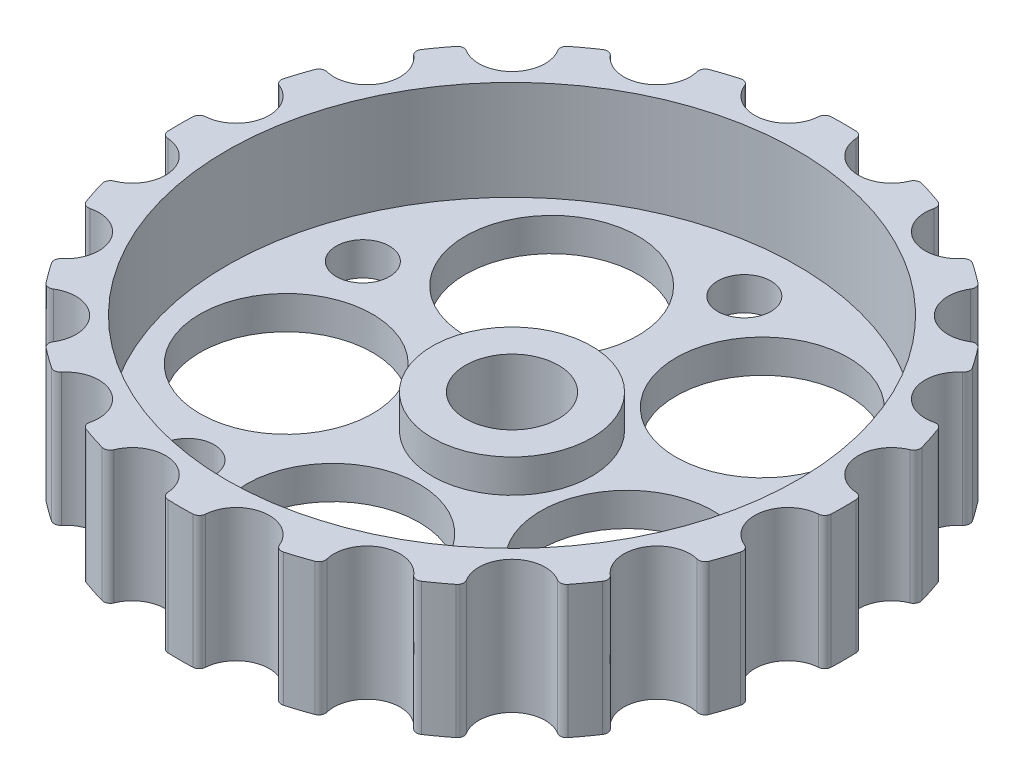
SolidWorks part; units mm, degrees
ref_plane "Спереди" through (0, 0, 0) normal (0, 0, 1) x (1, 0, 0)
ref_plane "Сверху" through (0, 0, 0) normal (0, 1, 0) x (1, 0, 0)
ref_plane "Справа" through (0, 0, 0) normal (1, 0, 0) x (0, 0, -1)
sketch "Эскиз1" plane through (0, 0, 0) normal (0, 0, 1) x (1, 0, 0)
  line L1 (50, -10) -> (0, -10)
  line L2 (50, -10) -> (50, 10)
  line L3 (50, 10) -> (0, 10)
  line L4 (0, -10) -> (0, 10)
  line L5 (50, -10) -> (0, 10) construction
  line L6 (50, 10) -> (0, -10) construction
  point P0 (25, 0)
  dimension "D1" = 20
  dimension "D2" = 50
revolve "Повернуть1" add sketch "Эскиз1" angle 360 about L4
sketch "Эскиз2" plane through (0, 10, 0) normal (0, 1, 0) x (1, 0, 0)
  line L0 (0, 50) -> (0, 0) construction
  line L1 (0, 0) -> (35.3553, 35.3553) construction
  circle A0 centre (0, 0) radius 50 construction
  dimension "D1" = 45
ref_plane "Плоскость1" through (0, 0, 0) normal (0.7071, 0, 0.7071) x (0.7071, 0, -0.7071)
sketch "Эскиз3" plane through (0, 0, 0) normal (0.7071, 0, 0.7071) x (0.7071, 0, -0.7071)
  line L0 (50, -10) -> (50, 10) construction
  line L1 (45, -10) -> (55, -10) construction
  line L2 (45, -10) -> (45, 10) construction
  line L3 (45, 10) -> (55, 10) construction
  line L4 (55, -10) -> (55, 10)
  line L5 (45, -10) -> (55, 10) construction
  line L6 (45, 10) -> (55, -10) construction
  line L7 (0, 10) -> (50, 10) construction
  line L8 (50, 10) -> (50, -10)
  line L9 (50, 10) -> (50, -10)
  line L10 (50, 10) -> (55, 10)
  line L11 (50, -10) -> (55, -10)
  point P0 (50, 0)
  dimension "D1" = 10
revolve "Вырез-Повернуть1" cut sketch "Эскиз3" angle 360 about L8
sketch "Эскиз4" plane through (0, 0, 0) normal (1, 0, 0) x (0, 0, -1)
  line L0 (0, 10) -> (0, 0)
  line L1 (50, 10) -> (-50, 10) construction
  line L2 (0, 0) -> (12, 0)
  line L3 (12, 0) -> (12, -5)
  line L4 (12, -5) -> (43, -5)
  line L5 (43, -5) -> (43, 10)
  line L6 (43, 10) -> (0, 10)
  dimension "D1" = 43
  dimension "D2" = 5
  dimension "D3" = 12
revolve "Вырез-Повернуть4" cut sketch "Эскиз4" angle 360 about L0
fillet "Скругление1" radius 1 2 edges at (38.7097, 0, -31.6475) (31.6475, 0, -38.7097)
pattern_circular "Круговой массив1" count 20 over 360 about axis through (0, 0, 0) along (0, 1, 0) of "Вырез-Повернуть1", "Скругление1"
sketch "Эскиз6" plane through (0, 0, 0) normal (1, 0, 0) x (0, 0, -1)
  line L0 (-26.5296, -10) -> (-17.6995, -10) construction
  line L1 (-27, -10) -> (-40, -10)
  line L2 (-27, -10) -> (-27, 10)
  line L3 (-27, 10) -> (-40, 10)
  line L4 (-40, -10) -> (-40, 10)
  line L5 (-30.3553, 10) -> (-38.0047, 10) construction
  dimension "D1" = 27
  dimension "D2" = 13
revolve "Вырез-Повернуть5" cut sketch "Эскиз6" angle 360 about L2
sketch "Эскиз7" plane through (0, -10, 0) normal (0, -1, 0) x (1, 0, 0)
  circle A0 centre (0, 0) radius 7
  dimension "D1" = 14
extrude "Вырез-Вытянуть1" cut sketch "Эскиз7" against normal through all
pattern_circular "Круговой массив2" count 5 over 360 about axis through (0, 0, 0) along (0, 1, 0) of "Вырез-Повернуть5"
sketch "Эскиз8" plane through (0, 0, 0) normal (1, 0, 0) x (0, 0, -1)
  line L0 (39.5503, -10) -> (45.7597, -10) construction
  line L1 (39, -10) -> (35, -10)
  line L2 (39, -10) -> (39, 10)
  line L3 (39, 10) -> (35, 10)
  line L4 (35, -10) -> (35, 10)
  line L5 (38.0047, 10) -> (30.3553, 10) construction
  dimension "D1" = 35
  dimension "D2" = 4
revolve "Вырез-Повернуть6" cut sketch "Эскиз8" angle 360 about L4
pattern_circular "Круговой массив3" count 5 over 360 about axis through (0, 0, 0) along (0, 1, 0) of "Вырез-Повернуть6"
